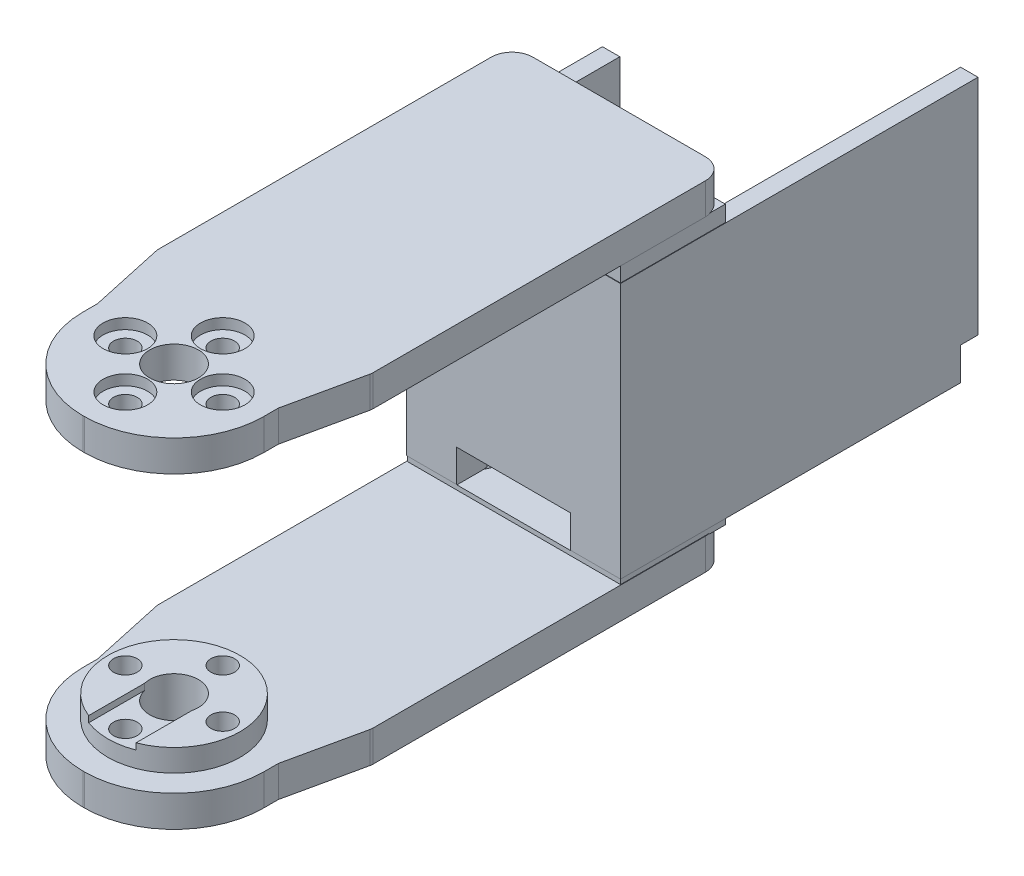
SolidWorks part; units mm, degrees
ref_plane "Front Plane" through (0, 0, 0) normal (0, 0, 1) x (1, 0, 0)
ref_plane "Top Plane" through (0, 0, 0) normal (0, 1, 0) x (1, 0, 0)
ref_plane "Right Plane" through (0, 0, 0) normal (1, 0, 0) x (0, 0, -1)
ref_plane "PY_p18_800" through (0, 18.8, 0) normal (0, 1, 0) x (1, 0, 0)
sketch "S_prism1" plane through (0, 18.8, 0) normal (0, 1, 0) x (1, 0, 0)
  line L0 (-13, 2) -> (-15.354, 12.7893)
  line L1 (-15.4, 13.2156) -> (-15.4, 61)
  line L2 (-12.4, 64) -> (12.4, 64)
  line L3 (15.4, 61) -> (15.4, 13.2156)
  line L4 (15.354, 12.7893) -> (13, 2)
  line L5 (13, 2) -> (13, -0.1)
  line L6 (0.1, -13) -> (-0.1, -13)
  line L7 (-13, -0.1) -> (-13, 2)
  arc A0 (-15.354, 12.7893) -> (-15.4, 13.2156) centre (-13.4076, 13.215) cw
  arc A1 (-15.4, 61) -> (-12.4, 64) centre (-12.3999, 60.9999) cw
  arc A2 (12.4, 64) -> (15.4, 61) centre (12.3999, 60.9999) cw
  arc A3 (15.4, 13.2156) -> (15.354, 12.7893) centre (13.4076, 13.215) cw
  arc A4 (13, -0.1) -> (0.1, -13) centre (0.1001, -0.1001) cw
  arc A5 (-0.1, -13) -> (-13, -0.1) centre (-0.1001, -0.1001) cw
extrude "Boss_1" add sketch "S_prism1" along normal blind 4.5
ref_plane "PY_m20_950" through (0, -20.95, 0) normal (0, 1, 0) x (1, 0, 0)
sketch "S_cyl2" plane through (0, -20.95, 0) normal (0, 1, 0) x (1, 0, 0)
  circle A0 centre (0, 0) radius 9.5
  dimension "D1_S_cyl2" = 19
extrude "Boss_2" add sketch "S_cyl2" along normal blind 3.2
ref_plane "PY_m25_450" through (0, -25.45, 0) normal (0, 1, 0) x (1, 0, 0)
sketch "S_prism3" plane through (0, -25.45, 0) normal (0, 1, 0) x (1, 0, 0)
  line L0 (-13, 2) -> (-15.354, 12.7893)
  line L1 (-15.4, 13.2156) -> (-15.4, 61)
  line L2 (-12.4, 64) -> (12.4, 64)
  line L3 (15.4, 61) -> (15.4, 13.2156)
  line L4 (15.354, 12.7893) -> (13, 2)
  line L5 (13, 2) -> (13, -0.1)
  line L6 (0.1, -13) -> (-0.1, -13)
  line L7 (-13, -0.1) -> (-13, 2)
  arc A0 (-15.354, 12.7893) -> (-15.4, 13.2156) centre (-13.4076, 13.215) cw
  arc A1 (-15.4, 61) -> (-12.4, 64) centre (-12.3999, 60.9999) cw
  arc A2 (12.4, 64) -> (15.4, 61) centre (12.3999, 60.9999) cw
  arc A3 (15.4, 13.2156) -> (15.354, 12.7893) centre (13.4076, 13.215) cw
  arc A4 (13, -0.1) -> (0.1, -13) centre (0.1001, -0.1001) cw
  arc A5 (-0.1, -13) -> (-13, -0.1) centre (-0.1001, -0.1001) cw
extrude "Boss_3" add sketch "S_prism3" along normal blind 4.5
ref_plane "PZ_m51_300" through (0, 0, -51.3) normal (0, 0, 1) x (1, 0, 0)
sketch "S_box4" plane through (0, 0, -51.3) normal (0, 0, 1) x (1, 0, 0)
  line L0 (-15.4, -20.2) -> (15.4, -20.2)
  line L1 (15.4, -20.2) -> (15.4, 16.6)
  line L2 (15.4, 16.6) -> (-15.4, 16.6)
  line L3 (-15.4, 16.6) -> (-15.4, -20.2)
  dimension "P1" = 15.4
  dimension "P2" = 20.2
  dimension "P3" = 15.4
  dimension "P4" = 20.2
  dimension "P5" = 15.4
  dimension "P6" = 16.6
  dimension "P7" = 15.4
  dimension "P8" = 16.6
extrude "Boss_4" add sketch "S_box4" along normal blind 2.5
ref_plane "PZ_m100_200" through (0, 0, -100.2) normal (0, 0, 1) x (1, 0, 0)
sketch "S_box5" plane through (0, 0, -100.2) normal (0, 0, 1) x (1, 0, 0)
  line L0 (12.9, -20.2) -> (15.4, -20.2)
  line L1 (15.4, -20.2) -> (15.4, 16.6)
  line L2 (15.4, 16.6) -> (12.9, 16.6)
  line L3 (12.9, 16.6) -> (12.9, -20.2)
  dimension "P1" = 12.9
  dimension "P2" = 20.2
  dimension "P3" = 15.4
  dimension "P4" = 20.2
  dimension "P5" = 15.4
  dimension "P6" = 16.6
  dimension "P7" = 12.9
  dimension "P8" = 16.6
extrude "Boss_5" add sketch "S_box5" along normal blind 51.4
sketch "S_box6" plane through (0, 0, -100.2) normal (0, 0, 1) x (1, 0, 0)
  line L0 (-15.4, -20.2) -> (15.4, -20.2)
  line L1 (15.4, -20.2) -> (15.4, -15.6)
  line L2 (15.4, -15.6) -> (-15.4, -15.6)
  line L3 (-15.4, -15.6) -> (-15.4, -20.2)
  dimension "P1" = 15.4
  dimension "P2" = 20.2
  dimension "P3" = 15.4
  dimension "P4" = 20.2
  dimension "P5" = 15.4
  dimension "P6" = 15.6
  dimension "P7" = 15.4
  dimension "P8" = 15.6
extrude "Boss_6" add sketch "S_box6" along normal blind 51.4
ref_plane "PZ_m77_000" through (0, 0, -77) normal (0, 0, 1) x (1, 0, 0)
sketch "S_box7" plane through (0, 0, -77) normal (0, 0, 1) x (1, 0, 0)
  line L0 (-15.4, -20.2) -> (-12.9, -20.2)
  line L1 (-12.9, -20.2) -> (-12.9, 16.6)
  line L2 (-12.9, 16.6) -> (-15.4, 16.6)
  line L3 (-15.4, 16.6) -> (-15.4, -20.2)
  dimension "P1" = 15.4
  dimension "P2" = 20.2
  dimension "P3" = 12.9
  dimension "P4" = 20.2
  dimension "P5" = 12.9
  dimension "P6" = 16.6
  dimension "P7" = 15.4
  dimension "P8" = 16.6
extrude "Boss_7" add sketch "S_box7" along normal blind 28.2
ref_plane "PZ_m63_930" through (0, 0, -63.93) normal (0, 0, 1) x (1, 0, 0)
sketch "S_box8" plane through (0, 0, -63.93) normal (0, 0, 1) x (1, 0, 0)
  line L0 (-15.33, 16.5) -> (15.33, 16.5)
  line L1 (15.33, 16.5) -> (15.33, 18.9)
  line L2 (15.33, 18.9) -> (-15.33, 18.9)
  line L3 (-15.33, 18.9) -> (-15.33, 16.5)
  dimension "P1" = 15.33
  dimension "P2" = 16.5
  dimension "P3" = 15.33
  dimension "P4" = 16.5
  dimension "P5" = 15.33
  dimension "P6" = 18.9
  dimension "P7" = 15.33
  dimension "P8" = 18.9
extrude "Boss_8" add sketch "S_box8" along normal blind 15.06
sketch "S_box9" plane through (0, 0, -63.93) normal (0, 0, 1) x (1, 0, 0)
  line L0 (-15.33, -21.05) -> (15.33, -21.05)
  line L1 (15.33, -21.05) -> (15.33, -20.1)
  line L2 (15.33, -20.1) -> (-15.33, -20.1)
  line L3 (-15.33, -20.1) -> (-15.33, -21.05)
  dimension "P1" = 15.33
  dimension "P2" = 21.05
  dimension "P3" = 15.33
  dimension "P4" = 21.05
  dimension "P5" = 15.33
  dimension "P6" = 20.1
  dimension "P7" = 15.33
  dimension "P8" = 20.1
extrude "Boss_9" add sketch "S_box9" along normal blind 15.06
ref_plane "PY_p18_700" through (0, 18.7, 0) normal (0, 1, 0) x (1, 0, 0)
sketch "S_hole10" plane through (0, 18.7, 0) normal (0, 1, 0) x (1, 0, 0)
  circle A0 centre (0, 0) radius 3.5
  dimension "D1_S_hole10" = 7
extrude "Hole_10" cut sketch "S_hole10" along normal blind 4.7
sketch "S_hole11" plane through (0, 18.7, 0) normal (0, 1, 0) x (1, 0, 0)
  circle A0 centre (7, 0) radius 1.7
  dimension "D1_S_hole11" = 3.4
  dimension "P2" = 7
extrude "Hole_11" cut sketch "S_hole11" along normal blind 4.7
sketch "S_hole12" plane through (0, 18.7, 0) normal (0, 1, 0) x (1, 0, 0)
  circle A0 centre (0, -7) radius 1.7
  dimension "D1_S_hole12" = 3.4
  dimension "P2" = 7
extrude "Hole_12" cut sketch "S_hole12" along normal blind 4.7
sketch "S_hole13" plane through (0, 18.7, 0) normal (0, 1, 0) x (1, 0, 0)
  circle A0 centre (-7, 0) radius 1.7
  dimension "D1_S_hole13" = 3.4
  dimension "P2" = 7
extrude "Hole_13" cut sketch "S_hole13" along normal blind 4.7
sketch "S_hole14" plane through (0, 18.7, 0) normal (0, 1, 0) x (1, 0, 0)
  circle A0 centre (0, 7) radius 1.7
  dimension "D1_S_hole14" = 3.4
  dimension "P2" = 7
extrude "Hole_14" cut sketch "S_hole14" along normal blind 4.7
ref_plane "PY_p21_800" through (0, 21.8, 0) normal (0, 1, 0) x (1, 0, 0)
sketch "S_hole15" plane through (0, 21.8, 0) normal (0, 1, 0) x (1, 0, 0)
  circle A0 centre (7, 0) radius 3.2
  dimension "D1_S_hole15" = 6.4
  dimension "P2" = 7
extrude "Hole_15" cut sketch "S_hole15" along normal blind 1.6
sketch "S_hole16" plane through (0, 21.8, 0) normal (0, 1, 0) x (1, 0, 0)
  circle A0 centre (0, -7) radius 3.2
  dimension "D1_S_hole16" = 6.4
  dimension "P2" = 7
extrude "Hole_16" cut sketch "S_hole16" along normal blind 1.6
sketch "S_hole17" plane through (0, 21.8, 0) normal (0, 1, 0) x (1, 0, 0)
  circle A0 centre (-7, 0) radius 3.2
  dimension "D1_S_hole17" = 6.4
  dimension "P2" = 7
extrude "Hole_17" cut sketch "S_hole17" along normal blind 1.6
sketch "S_hole18" plane through (0, 21.8, 0) normal (0, 1, 0) x (1, 0, 0)
  circle A0 centre (0, 7) radius 3.2
  dimension "D1_S_hole18" = 6.4
  dimension "P2" = 7
extrude "Hole_18" cut sketch "S_hole18" along normal blind 1.6
ref_plane "PY_m25_550" through (0, -25.55, 0) normal (0, 1, 0) x (1, 0, 0)
sketch "S_hole19" plane through (0, -25.55, 0) normal (0, 1, 0) x (1, 0, 0)
  circle A0 centre (0, 0) radius 3.5
  dimension "D1_S_hole19" = 7
extrude "Hole_19" cut sketch "S_hole19" along normal blind 7.9
sketch "S_hole20" plane through (0, -25.55, 0) normal (0, 1, 0) x (1, 0, 0)
  circle A0 centre (7, 0) radius 1.7
  dimension "D1_S_hole20" = 3.4
  dimension "P2" = 7
extrude "Hole_20" cut sketch "S_hole20" along normal blind 7.9
sketch "S_hole21" plane through (0, -25.55, 0) normal (0, 1, 0) x (1, 0, 0)
  circle A0 centre (0, -7) radius 1.7
  dimension "D1_S_hole21" = 3.4
  dimension "P2" = 7
extrude "Hole_21" cut sketch "S_hole21" along normal blind 7.9
sketch "S_hole22" plane through (0, -25.55, 0) normal (0, 1, 0) x (1, 0, 0)
  circle A0 centre (-7, 0) radius 1.7
  dimension "D1_S_hole22" = 3.4
  dimension "P2" = 7
extrude "Hole_22" cut sketch "S_hole22" along normal blind 7.9
sketch "S_hole23" plane through (0, -25.55, 0) normal (0, 1, 0) x (1, 0, 0)
  circle A0 centre (0, 7) radius 1.7
  dimension "D1_S_hole23" = 3.4
  dimension "P2" = 7
extrude "Hole_23" cut sketch "S_hole23" along normal blind 7.9
sketch "S_hole24" plane through (0, -25.55, 0) normal (0, 1, 0) x (1, 0, 0)
  circle A0 centre (7, 0) radius 3.2
  dimension "D1_S_hole24" = 6.4
  dimension "P2" = 7
extrude "Hole_24" cut sketch "S_hole24" along normal blind 2.1
sketch "S_hole25" plane through (0, -25.55, 0) normal (0, 1, 0) x (1, 0, 0)
  circle A0 centre (0, -7) radius 3.2
  dimension "D1_S_hole25" = 6.4
  dimension "P2" = 7
extrude "Hole_25" cut sketch "S_hole25" along normal blind 2.1
sketch "S_hole26" plane through (0, -25.55, 0) normal (0, 1, 0) x (1, 0, 0)
  circle A0 centre (-7, 0) radius 3.2
  dimension "D1_S_hole26" = 6.4
  dimension "P2" = 7
extrude "Hole_26" cut sketch "S_hole26" along normal blind 2.1
sketch "S_hole27" plane through (0, -25.55, 0) normal (0, 1, 0) x (1, 0, 0)
  circle A0 centre (0, 7) radius 3.2
  dimension "D1_S_hole27" = 6.4
  dimension "P2" = 7
extrude "Hole_27" cut sketch "S_hole27" along normal blind 2.1
sketch "S_cut28" plane through (0, 0, 0) normal (0, 0, 1) x (1, 0, 0)
  line L0 (-3.4, -18.65) -> (3.4, -18.65)
  line L1 (3.4, -18.65) -> (3.4, -17.65)
  line L2 (3.4, -17.65) -> (-3.4, -17.65)
  line L3 (-3.4, -17.65) -> (-3.4, -18.65)
  dimension "P1" = 3.4
  dimension "P2" = 18.65
  dimension "P3" = 3.4
  dimension "P4" = 18.65
  dimension "P5" = 3.4
  dimension "P6" = 17.65
  dimension "P7" = 3.4
  dimension "P8" = 17.65
extrude "Pocket_28" cut sketch "S_cut28" along normal blind 10
ref_plane "PY_m20_300" through (0, -20.3, 0) normal (0, 1, 0) x (1, 0, 0)
sketch "S_hole29" plane through (0, -20.3, 0) normal (0, 1, 0) x (1, 0, 0)
  circle A0 centre (0, 87) radius 10.5
  dimension "D1_S_hole29" = 21
  dimension "P2" = 87
extrude "Hole_29" cut sketch "S_hole29" along normal blind 4.8
ref_plane "PZ_m76_100" through (0, 0, -76.1) normal (0, 0, 1) x (1, 0, 0)
sketch "S_cut30" plane through (0, 0, -76.1) normal (0, 0, 1) x (1, 0, 0)
  line L0 (-9.7, -20.3) -> (9.7, -20.3)
  line L1 (9.7, -20.3) -> (9.7, -15.55)
  line L2 (9.7, -15.55) -> (-9.7, -15.55)
  line L3 (-9.7, -15.55) -> (-9.7, -20.3)
  dimension "P1" = 9.7
  dimension "P2" = 20.3
  dimension "P3" = 9.7
  dimension "P4" = 20.3
  dimension "P5" = 9.7
  dimension "P6" = 15.55
  dimension "P7" = 9.7
  dimension "P8" = 15.55
extrude "Pocket_30" cut sketch "S_cut30" along normal blind 19.5
ref_plane "PZ_m56_600" through (0, 0, -56.6) normal (0, 0, 1) x (1, 0, 0)
sketch "S_cut31" plane through (0, 0, -56.6) normal (0, 0, 1) x (1, 0, 0)
  line L0 (-8.2, -20.3) -> (8.2, -20.3)
  line L1 (8.2, -20.3) -> (8.2, -15.55)
  line L2 (8.2, -15.55) -> (-8.2, -15.55)
  line L3 (-8.2, -15.55) -> (-8.2, -20.3)
  dimension "P1" = 8.2
  dimension "P2" = 20.3
  dimension "P3" = 8.2
  dimension "P4" = 20.3
  dimension "P5" = 8.2
  dimension "P6" = 15.55
  dimension "P7" = 8.2
  dimension "P8" = 15.55
extrude "Pocket_31" cut sketch "S_cut31" along normal blind 8.3
ref_plane "PZ_m87_000" through (0, 0, -87) normal (0, 0, 1) x (1, 0, 0)
sketch "S_cut32" plane through (0, 0, -87) normal (0, 0, 1) x (1, 0, 0)
  line L0 (-3.5, -20.3) -> (3.5, -20.3)
  line L1 (3.5, -20.3) -> (3.5, -15.55)
  line L2 (3.5, -15.55) -> (-3.5, -15.55)
  line L3 (-3.5, -15.55) -> (-3.5, -20.3)
  dimension "P1" = 3.5
  dimension "P2" = 20.3
  dimension "P3" = 3.5
  dimension "P4" = 20.3
  dimension "P5" = 3.5
  dimension "P6" = 15.55
  dimension "P7" = 3.5
  dimension "P8" = 15.55
extrude "Pocket_32" cut sketch "S_cut32" along normal blind 11
ref_plane "PZ_m100_700" through (0, 0, -100.7) normal (0, 0, 1) x (1, 0, 0)
sketch "S_cut33" plane through (0, 0, -100.7) normal (0, 0, 1) x (1, 0, 0)
  line L0 (-10, -20.4) -> (10, -20.4)
  line L1 (10, -20.4) -> (10, -17.5)
  line L2 (10, -17.5) -> (-10, -17.5)
  line L3 (-10, -17.5) -> (-10, -20.4)
  dimension "P1" = 10
  dimension "P2" = 20.4
  dimension "P3" = 10
  dimension "P4" = 20.4
  dimension "P5" = 10
  dimension "P6" = 17.5
  dimension "P7" = 10
  dimension "P8" = 17.5
extrude "Pocket_33" cut sketch "S_cut33" along normal blind 13.7
sketch "S_hole34" plane through (0, -20.3, 0) normal (0, 1, 0) x (1, 0, 0)
  circle A0 centre (-10.25, 54.25) radius 1.1
  dimension "D1_S_hole34" = 2.2
  dimension "P2" = 10.25
  dimension "P3" = 54.25
extrude "Hole_34" cut sketch "S_hole34" along normal blind 4.8
sketch "S_hole35" plane through (0, -20.3, 0) normal (0, 1, 0) x (1, 0, 0)
  circle A0 centre (-10.25, 54.25) radius 2.3
  dimension "D1_S_hole35" = 4.6
  dimension "P2" = 10.25
  dimension "P3" = 54.25
extrude "Hole_35" cut sketch "S_hole35" along normal blind 1.7
sketch "S_hole36" plane through (0, -20.3, 0) normal (0, 1, 0) x (1, 0, 0)
  circle A0 centre (10.25, 54.25) radius 1.1
  dimension "D1_S_hole36" = 2.2
  dimension "P2" = 10.25
  dimension "P3" = 54.25
extrude "Hole_36" cut sketch "S_hole36" along normal blind 4.8
sketch "S_hole37" plane through (0, -20.3, 0) normal (0, 1, 0) x (1, 0, 0)
  circle A0 centre (10.25, 54.25) radius 2.3
  dimension "D1_S_hole37" = 4.6
  dimension "P2" = 10.25
  dimension "P3" = 54.25
extrude "Hole_37" cut sketch "S_hole37" along normal blind 1.7
ref_plane "PZ_m100_300" through (0, 0, -100.3) normal (0, 0, 1) x (1, 0, 0)
sketch "S_cut38" plane through (0, 0, -100.3) normal (0, 0, 1) x (1, 0, 0)
  line L0 (-15.5, -20.3) -> (15.5, -20.3)
  line L1 (15.5, -20.3) -> (15.5, -15.5)
  line L2 (15.5, -15.5) -> (-15.5, -15.5)
  line L3 (-15.5, -15.5) -> (-15.5, -20.3)
  dimension "P1" = 15.5
  dimension "P2" = 20.3
  dimension "P3" = 15.5
  dimension "P4" = 20.3
  dimension "P5" = 15.5
  dimension "P6" = 15.5
  dimension "P7" = 15.5
  dimension "P8" = 15.5
extrude "Pocket_38" cut sketch "S_cut38" along normal blind 2.6
ref_plane "PZ_m97_800" through (0, 0, -97.8) normal (0, 0, 1) x (1, 0, 0)
sketch "S_cut39" plane through (0, 0, -97.8) normal (0, 0, 1) x (1, 0, 0)
  line L0 (-9.5, -20.3) -> (9.5, -20.3)
  line L1 (9.5, -20.3) -> (9.5, -15.55)
  line L2 (9.5, -15.55) -> (-9.5, -15.55)
  line L3 (-9.5, -15.55) -> (-9.5, -20.3)
  dimension "P1" = 9.5
  dimension "P2" = 20.3
  dimension "P3" = 9.5
  dimension "P4" = 20.3
  dimension "P5" = 9.5
  dimension "P6" = 15.55
  dimension "P7" = 9.5
  dimension "P8" = 15.55
extrude "Pocket_39" cut sketch "S_cut39" along normal blind 22.2
ref_plane "PZ_m78_900" through (0, 0, -78.9) normal (0, 0, 1) x (1, 0, 0)
sketch "S_cut40" plane through (0, 0, -78.9) normal (0, 0, 1) x (1, 0, 0)
  line L0 (-7.5, 16.2) -> (7.5, 16.2)
  line L1 (7.5, 16.2) -> (7.5, 17.75)
  line L2 (7.5, 17.75) -> (-7.5, 17.75)
  line L3 (-7.5, 17.75) -> (-7.5, 16.2)
  dimension "P1" = 7.5
  dimension "P2" = 16.2
  dimension "P3" = 7.5
  dimension "P4" = 16.2
  dimension "P5" = 7.5
  dimension "P6" = 17.75
  dimension "P7" = 7.5
  dimension "P8" = 17.75
extrude "Pocket_40" cut sketch "S_cut40" along normal blind 27.4
sketch "S_hole41" plane through (0, -25.55, 0) normal (0, 1, 0) x (1, 0, 0)
  circle A0 centre (-10.25, 54.25) radius 2.5
  dimension "D1_S_hole41" = 5
  dimension "P2" = 10.25
  dimension "P3" = 54.25
extrude "Hole_41" cut sketch "S_hole41" along normal blind 5.3
sketch "S_hole42" plane through (0, -25.55, 0) normal (0, 1, 0) x (1, 0, 0)
  circle A0 centre (10.25, 54.25) radius 2.5
  dimension "D1_S_hole42" = 5
  dimension "P2" = 10.25
  dimension "P3" = 54.25
extrude "Hole_42" cut sketch "S_hole42" along normal blind 5.3
equation "\"plate_t\" = 3"
equation "\"clearance\" = 0.5"
